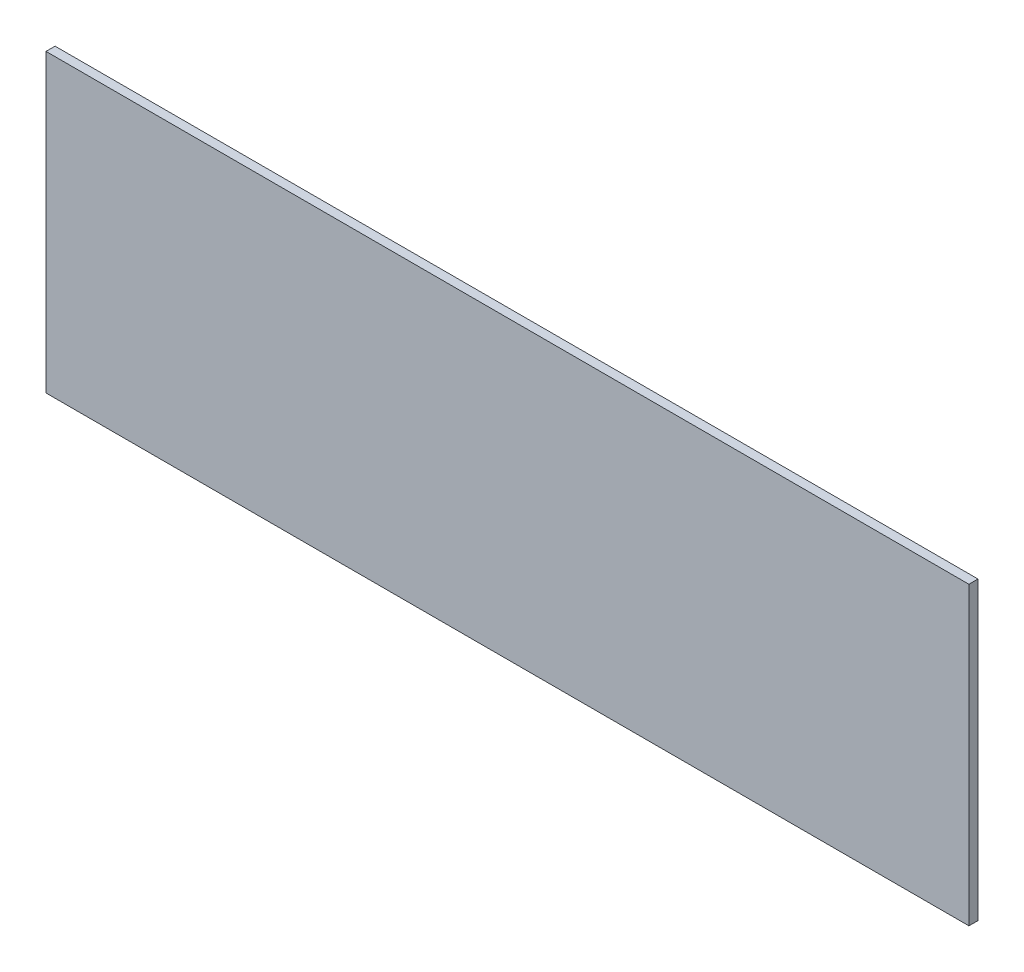
SolidWorks part; units mm, degrees
ref_plane "前视基准面" through (0, 0, 0) normal (0, 0, 1) x (1, 0, 0)
ref_plane "上视基准面" through (0, 0, 0) normal (0, 1, 0) x (1, 0, 0)
ref_plane "右视基准面" through (0, 0, 0) normal (1, 0, 0) x (0, 0, -1)
sketch "草图1" plane through (0, 0, 0) normal (0, 0, 1) x (1, 0, 0)
  line L1 (-48.3059, 34.6047) -> (53.3404, 34.6047)
  line L2 (-48.3059, 34.6047) -> (-48.3059, 2.0221)
  line L3 (-48.3059, 2.0221) -> (53.3404, 2.0221)
  line L4 (53.3404, 34.6047) -> (53.3404, 2.0221)
  point P4 (26.8801, 2.1486)
  point P5 (53.3404, 2.0221)
extrude "凸台-拉伸1" add sketch "草图1" along normal blind 1
